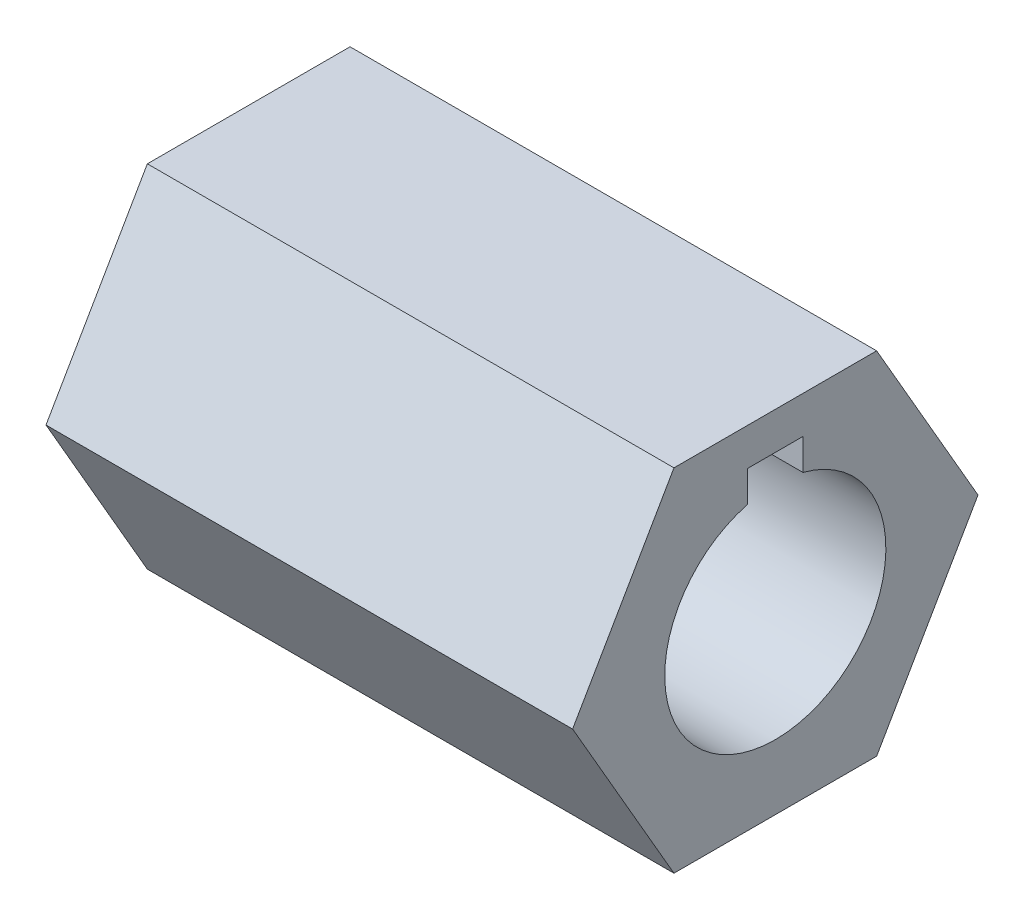
SolidWorks part; units mm, degrees
material "AISI 1045 Steel, cold drawn"
ref_plane "Front Plane" through (0, 0, 0) normal (0, 0, 1) x (1, 0, 0)
ref_plane "Top Plane" through (0, 0, 0) normal (0, 1, 0) x (1, 0, 0)
ref_plane "Right Plane" through (0, 0, 0) normal (1, 0, 0) x (0, 0, -1)
sketch "Sketch1" plane through (0, 0, 0) normal (1, 0, 0) x (0, 0, -1)
  line L1 (7.3323, 0) -> (3.6662, 6.35)
  line L2 (3.6662, 6.35) -> (-3.6662, 6.35)
  line L3 (-3.6662, 6.35) -> (-7.3323, 0)
  line L4 (-7.3323, 0) -> (-3.6662, -6.35)
  line L5 (-3.6662, -6.35) -> (3.6662, -6.35)
  line L6 (3.6662, -6.35) -> (7.3323, 0)
  circle A0 centre (0, 0) radius 6.35 construction
  dimension "D1" = 12.7
extrude "Boss-Extrude1" add sketch "Sketch1" along normal blind 19.05
sketch "Sketch2" plane through (19.05, 0, 0) normal (1, 0, 0) x (0, 0, -1)
  line L1 (1, 3) -> (-1, 3)
  line L2 (1, 3) -> (1, 5)
  line L3 (1, 5) -> (-1, 5)
  line L4 (-1, 3) -> (-1, 5)
  line L5 (1, 3) -> (-1, 5) construction
  line L6 (1, 5) -> (-1, 3) construction
  circle A0 centre (0, 0) radius 4
  point P3 (0, 4)
  dimension "D1" = 8
  dimension "D2" = 2
  dimension "D3" = 2
extrude "Cut-Extrude1" cut sketch "Sketch2" against normal through all contours A0 L2 L3 L4 | L4 A0 L2 L1 | L2 A0 L4 L1
